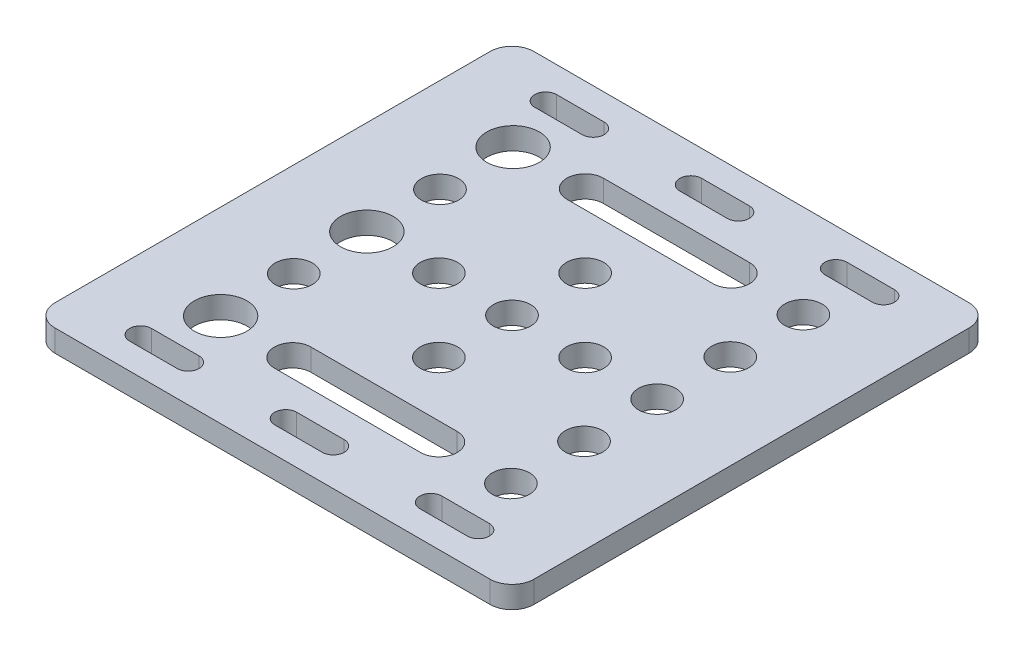
SolidWorks part; units mm, degrees
ref_plane "前视基准面" through (0, 0, 0) normal (0, 0, 1) x (1, 0, 0)
ref_plane "上视基准面" through (0, 0, 0) normal (0, 1, 0) x (1, 0, 0)
ref_plane "右视基准面" through (0, 0, 0) normal (1, 0, 0) x (0, 0, -1)
other "Configuration Table"
sketch "草图1" plane through (0, 0, 0) normal (0, 1, 0) x (1, 0, 0)
  line L0 (-39.3983, -32.75) -> (100.1222, -32.75) construction
  line L1 (0, 0) -> (65.5, 0)
  line L2 (0, 0) -> (0, -65.5)
  line L3 (0, -65.5) -> (65.5, -65.5)
  line L4 (65.5, 0) -> (65.5, -65.5)
  line L5 (32.75, 44.7376) -> (32.75, -74.3597) construction
  line L6 (29.5, -5.05) -> (36, -5.05) construction
  line L7 (29.5, -3.55) -> (36, -3.55)
  line L8 (29.5, -6.55) -> (36, -6.55)
  line L9 (49.35, -5.05) -> (55.85, -5.05) construction
  line L10 (49.35, -3.55) -> (55.85, -3.55)
  line L11 (49.35, -6.55) -> (55.85, -6.55)
  line L12 (16.15, -5.05) -> (9.65, -5.05) construction
  line L13 (16.15, -3.55) -> (9.65, -3.55)
  line L14 (16.15, -6.55) -> (9.65, -6.55)
  line L15 (16.15, -60.45) -> (9.65, -60.45) construction
  line L16 (16.15, -61.95) -> (9.65, -61.95)
  line L17 (16.15, -58.95) -> (9.65, -58.95)
  line L18 (29.5, -60.45) -> (36, -60.45) construction
  line L19 (29.5, -61.95) -> (36, -61.95)
  line L20 (29.5, -58.95) -> (36, -58.95)
  line L21 (49.35, -60.45) -> (55.85, -60.45) construction
  line L22 (49.35, -61.95) -> (55.85, -61.95)
  line L23 (49.35, -58.95) -> (55.85, -58.95)
  line L24 (22.75, -12.75) -> (42.75, -12.75) construction
  line L25 (22.75, -10.25) -> (42.75, -10.25)
  line L26 (22.75, -15.25) -> (42.75, -15.25)
  line L27 (22.75, -52.75) -> (42.75, -52.75) construction
  line L28 (22.75, -55.25) -> (42.75, -55.25)
  line L29 (22.75, -50.25) -> (42.75, -50.25)
  line L30 (12.9, -12.75) -> (12.9, -32.75) construction
  line L31 (52.6, -12.75) -> (52.6, -22.75) construction
  arc A0 (29.5, -3.55) -> (29.5, -6.55) centre (29.5, -5.05) ccw
  arc A1 (36, -6.55) -> (36, -3.55) centre (36, -5.05) ccw
  arc A2 (49.35, -3.55) -> (49.35, -6.55) centre (49.35, -5.05) ccw
  arc A3 (55.85, -6.55) -> (55.85, -3.55) centre (55.85, -5.05) ccw
  arc A4 (16.15, -3.55) -> (16.15, -6.55) centre (16.15, -5.05) cw
  arc A5 (9.65, -6.55) -> (9.65, -3.55) centre (9.65, -5.05) cw
  arc A6 (16.15, -61.95) -> (16.15, -58.95) centre (16.15, -60.45) ccw
  arc A7 (9.65, -58.95) -> (9.65, -61.95) centre (9.65, -60.45) ccw
  arc A8 (29.5, -61.95) -> (29.5, -58.95) centre (29.5, -60.45) cw
  arc A9 (36, -58.95) -> (36, -61.95) centre (36, -60.45) cw
  arc A10 (49.35, -61.95) -> (49.35, -58.95) centre (49.35, -60.45) cw
  arc A11 (55.85, -58.95) -> (55.85, -61.95) centre (55.85, -60.45) cw
  arc A12 (22.75, -10.25) -> (22.75, -15.25) centre (22.75, -12.75) ccw
  arc A13 (42.75, -15.25) -> (42.75, -10.25) centre (42.75, -12.75) ccw
  arc A14 (22.75, -55.25) -> (22.75, -50.25) centre (22.75, -52.75) cw
  arc A15 (42.75, -50.25) -> (42.75, -55.25) centre (42.75, -52.75) cw
  circle A16 centre (12.9, -12.75) radius 3.6
  circle A17 centre (12.9, -32.75) radius 3.6
  circle A18 centre (12.9, -52.75) radius 3.6
  circle A19 centre (32.75, -32.75) radius 2.55
  circle A20 centre (22.75, -32.75) radius 2.55
  circle A21 centre (32.75, -22.75) radius 2.55
  circle A22 centre (32.75, -42.75) radius 2.55
  circle A23 centre (42.75, -32.75) radius 2.55
  circle A24 centre (52.6, -12.75) radius 2.55
  circle A25 centre (52.6, -22.75) radius 2.55
  circle A26 centre (52.6, -32.75) radius 2.55
  circle A27 centre (52.6, -42.75) radius 2.55
  circle A28 centre (52.6, -52.75) radius 2.55
  circle A29 centre (12.9, -42.75) radius 2.55
  circle A30 centre (12.9, -22.75) radius 2.55
  point P9 (32.75, 0)
  point P10 (0, -32.75)
  point P13 (32.75, -5.05)
  point P20 (52.6, -5.05)
  point P27 (12.9, -5.05)
  point P34 (12.9, -60.45)
  point P41 (32.75, -60.45)
  point P48 (52.6, -60.45)
  point P55 (32.75, -12.75)
  point P63 (32.75, -52.75)
  dimension "D9" = 7.2
  dimension "D12" = 5.1
  dimension "D13" = 10
  dimension "D14" = 10
  dimension "D1" = 65.5
  dimension "D2" = 3
  dimension "D3" = 6.5
  dimension "D4" = 5.05
  dimension "D5" = 52.6
  dimension "D6" = 5
  dimension "D7" = 12.75
  dimension "D8" = 20
  dimension "D11" = 20
  dimension "D16" = 10
  dimension "D10" = 3
  dimension "D15" = 5
extrude "凸台-拉伸1" add sketch "草图1" along normal blind 3
fillet "圆角1" radius 3 4 edges at (65.5, 1.5, 0) (0, 1.5, 0) (0, 1.5, 65.5) (65.5, 1.5, 65.5)
